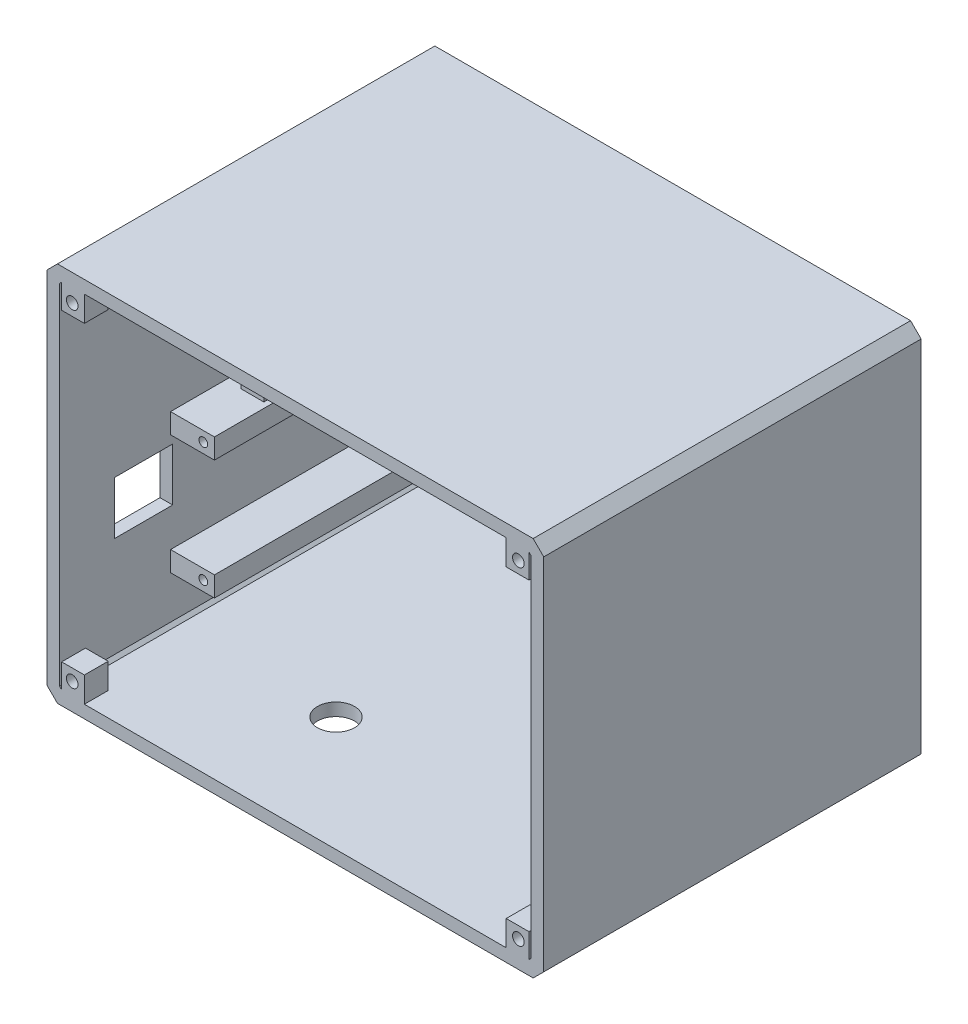
SolidWorks part; units mm, degrees
ref_plane "前视基准面" through (0, 0, 0) normal (0, 0, 1) x (1, 0, 0)
ref_plane "上视基准面" through (0, 0, 0) normal (0, 1, 0) x (1, 0, 0)
ref_plane "右视基准面" through (0, 0, 0) normal (1, 0, 0) x (0, 0, -1)
other "Configuration Table"
sketch "盒底及贯穿安装孔 profile" plane through (0, 0, 0) normal (0, 0, 1) x (1, 0, 0)
  line L0 (-45, -36) -> (45, -36)
  line L1 (45, -36) -> (47, -34)
  line L2 (47, -34) -> (47, 34)
  line L3 (47, 34) -> (45, 36)
  line L4 (45, 36) -> (-45, 36)
  line L5 (-45, 36) -> (-47, 34)
  line L6 (-47, 34) -> (-47, -34)
  line L7 (-47, -34) -> (-45, -36)
  line L8 (-1.8, -33.5) -> (3.8, -33.5)
  line L9 (3.8, -32.1) -> (-1.8, -32.1)
  line L10 (-1.6, 1.2) -> (3.6, 1.2)
  line L11 (3.6, 3) -> (-1.6, 3)
  circle A0 centre (21.1, 3.4) radius 1.3
  circle A1 centre (41.6, 3.4) radius 1.3
  circle A2 centre (-32, 27.5) radius 1.1
  circle A3 centre (-13, 27.5) radius 1.1
  circle A4 centre (-41, -10) radius 2.1
  circle A5 centre (41, -10) radius 2.1
  circle A6 centre (-42, 15) radius 2.1
  circle A7 centre (42, 15) radius 2.1
  arc A8 (3.8, -33.5) -> (3.8, -32.1) centre (3.8, -32.8) ccw
  arc A9 (-1.8, -32.1) -> (-1.8, -33.5) centre (-1.8, -32.8) ccw
  arc A10 (3.6, 1.2) -> (3.6, 3) centre (3.6, 2.1) ccw
  arc A11 (-1.6, 3) -> (-1.6, 1.2) centre (-1.6, 2.1) ccw
extrude "盒底及贯穿安装孔" add sketch "盒底及贯穿安装孔 profile" along normal blind 2.8
sketch "2.4 mm周壁 profile" plane through (0, 0, 0) normal (0, 0, 1) x (1, 0, 0)
  line L0 (-45, -36) -> (45, -36)
  line L1 (45, -36) -> (47, -34)
  line L2 (47, -34) -> (47, 34)
  line L3 (47, 34) -> (45, 36)
  line L4 (45, 36) -> (-45, 36)
  line L5 (-45, 36) -> (-47, 34)
  line L6 (-47, 34) -> (-47, -34)
  line L7 (-47, -34) -> (-45, -36)
  line L8 (-44, -33.6) -> (44, -33.6)
  line L9 (44, -33.6) -> (44.6, -33)
  line L10 (44.6, -33) -> (44.6, 33)
  line L11 (44.6, 33) -> (44, 33.6)
  line L12 (44, 33.6) -> (-44, 33.6)
  line L13 (-44, 33.6) -> (-44.6, 33)
  line L14 (-44.6, 33) -> (-44.6, -33)
  line L15 (-44.6, -33) -> (-44, -33.6)
extrude "2.4 mm周壁" add sketch "2.4 mm周壁 profile" along normal blind 68.6 from offset 2.8
sketch "盒盖上部连接耳 Ø2.2导孔 profile" plane through (0, 0, 0) normal (0, 0, 1) x (1, 0, 0)
  line L0 (-44.2, -34.1) -> (-39.9, -34.1)
  line L1 (-39.9, -34.1) -> (-39.9, -28.8)
  line L2 (-39.9, -28.8) -> (-44.2, -28.8)
  line L3 (-44.2, -28.8) -> (-44.2, -34.1)
  line L4 (-44.2, 28.8) -> (-39.9, 28.8)
  line L5 (-39.9, 28.8) -> (-39.9, 34.1)
  line L6 (-39.9, 34.1) -> (-44.2, 34.1)
  line L7 (-44.2, 34.1) -> (-44.2, 28.8)
  line L8 (39.9, -34.1) -> (44.2, -34.1)
  line L9 (44.2, -34.1) -> (44.2, -28.8)
  line L10 (44.2, -28.8) -> (39.9, -28.8)
  line L11 (39.9, -28.8) -> (39.9, -34.1)
  line L12 (39.9, 28.8) -> (44.2, 28.8)
  line L13 (44.2, 28.8) -> (44.2, 34.1)
  line L14 (44.2, 34.1) -> (39.9, 34.1)
  line L15 (39.9, 34.1) -> (39.9, 28.8)
  circle A0 centre (-42.2, -31) radius 1.1
  circle A1 centre (42.2, -31) radius 1.1
  circle A2 centre (-42.2, 31) radius 1.1
  circle A3 centre (42.2, 31) radius 1.1
extrude "盒盖上部连接耳 Ø2.2导孔" add sketch "盒盖上部连接耳 Ø2.2导孔 profile" along normal blind 4.5 from offset 66.9
sketch "电池垫条 profile" plane through (0, 0, 0) normal (0, 0, 1) x (1, 0, 0)
  line L0 (-28, -31.8) -> (-23, -31.8)
  line L1 (-23, -31.8) -> (-23, -0.3)
  line L2 (-23, -0.3) -> (-28, -0.3)
  line L3 (-28, -0.3) -> (-28, -31.8)
  line L4 (23, -31.8) -> (28, -31.8)
  line L5 (28, -31.8) -> (28, -0.3)
  line L6 (28, -0.3) -> (23, -0.3)
  line L7 (23, -0.3) -> (23, -31.8)
extrude "电池垫条" add sketch "电池垫条 profile" along normal blind 1.2 from offset 2.8
sketch "电池端挡 profile" plane through (0, 0, 0) normal (0, 0, 1) x (1, 0, 0)
  line L0 (-36.5, -31.4) -> (-34.9, -31.4)
  line L1 (-34.9, -31.4) -> (-34.9, -28)
  line L2 (-34.9, -28) -> (-36.5, -28)
  line L3 (-36.5, -28) -> (-36.5, -31.4)
  line L4 (34.9, -31.4) -> (36.5, -31.4)
  line L5 (36.5, -31.4) -> (36.5, -28)
  line L6 (36.5, -28) -> (34.9, -28)
  line L7 (34.9, -28) -> (34.9, -31.4)
extrude "电池端挡" add sketch "电池端挡 profile" along normal blind 3 from offset 2.8
sketch "传感器无排针侧支柱 Ø2.2 贯穿 profile" plane through (0, 0, 0) normal (0, 0, 1) x (1, 0, 0)
  circle A0 centre (-32, 27.5) radius 2.7
  circle A1 centre (-13, 27.5) radius 2.7
  circle A2 centre (-32, 27.5) radius 1.1
  circle A3 centre (-13, 27.5) radius 1.1
extrude "传感器无排针侧支柱 Ø2.2 贯穿" add sketch "传感器无排针侧支柱 Ø2.2 贯穿 profile" along normal blind 11.2 from offset 2.8
sketch "GNSS单边凸台 Ø2.6 贯穿，板内接触3mm profile" plane through (0, 0, 0) normal (0, 0, 1) x (1, 0, 0)
  line L0 (18.45, 1.2) -> (44.2, 1.2)
  line L1 (44.2, 1.2) -> (44.2, 5)
  line L2 (44.2, 5) -> (38.9, 5)
  line L3 (38.9, 5) -> (38.9, 2)
  line L4 (38.9, 2) -> (23.8, 2)
  line L5 (23.8, 2) -> (23.8, 5)
  line L6 (23.8, 5) -> (18.45, 5)
  line L7 (18.45, 5) -> (18.45, 1.2)
  circle A0 centre (21.1, 3.4) radius 1.3
  circle A1 centre (41.6, 3.4) radius 1.3
extrude "GNSS单边凸台 Ø2.6 贯穿，板内接触3mm" add sketch "GNSS单边凸台 Ø2.6 贯穿，板内接触3mm profile" along normal blind 6 from offset 2.8
sketch "上层端部支座根部 profile" plane through (0, 0, 0) normal (0, 0, 1) x (1, 0, 0)
  line L0 (36.3, -24.9) -> (44.9, -24.9)
  line L1 (44.9, -24.9) -> (44.9, -21.1)
  line L2 (44.9, -21.1) -> (36.3, -21.1)
  line L3 (36.3, -21.1) -> (36.3, -24.9)
  line L4 (-44.9, -24.9) -> (-36.3, -24.9)
  line L5 (-36.3, -24.9) -> (-36.3, -21.1)
  line L6 (-36.3, -21.1) -> (-44.9, -21.1)
  line L7 (-44.9, -21.1) -> (-44.9, -24.9)
  line L8 (36.3, -2.3) -> (44.9, -2.3)
  line L9 (44.9, -2.3) -> (44.9, 1.5)
  line L10 (44.9, 1.5) -> (36.3, 1.5)
  line L11 (36.3, 1.5) -> (36.3, -2.3)
  line L12 (-44.9, -2.3) -> (-36.3, -2.3)
  line L13 (-36.3, -2.3) -> (-36.3, 1.5)
  line L14 (-36.3, 1.5) -> (-44.9, 1.5)
  line L15 (-44.9, 1.5) -> (-44.9, -2.3)
extrude "上层端部支座根部" add sketch "上层端部支座根部 profile" along normal blind 41.6 from offset 2.8
sketch "上层端部支座 Ø1.65导孔 profile" plane through (0, 0, 0) normal (0, 0, 1) x (1, 0, 0)
  line L0 (36.3, -24.9) -> (44.9, -24.9)
  line L1 (44.9, -24.9) -> (44.9, -21.1)
  line L2 (44.9, -21.1) -> (36.3, -21.1)
  line L3 (36.3, -21.1) -> (36.3, -24.9)
  line L4 (-44.9, -24.9) -> (-36.3, -24.9)
  line L5 (-36.3, -24.9) -> (-36.3, -21.1)
  line L6 (-36.3, -21.1) -> (-44.9, -21.1)
  line L7 (-44.9, -21.1) -> (-44.9, -24.9)
  line L8 (36.3, -2.3) -> (44.9, -2.3)
  line L9 (44.9, -2.3) -> (44.9, 1.5)
  line L10 (44.9, 1.5) -> (36.3, 1.5)
  line L11 (36.3, 1.5) -> (36.3, -2.3)
  line L12 (-44.9, -2.3) -> (-36.3, -2.3)
  line L13 (-36.3, -2.3) -> (-36.3, 1.5)
  line L14 (-36.3, 1.5) -> (-44.9, 1.5)
  line L15 (-44.9, 1.5) -> (-44.9, -2.3)
  circle A0 centre (-38.4, -23) radius 0.825
  circle A1 centre (-38.4, -0.4) radius 0.825
  circle A2 centre (38.4, -23) radius 0.825
  circle A3 centre (38.4, -0.4) radius 0.825
extrude "上层端部支座 Ø1.65导孔" add sketch "上层端部支座 Ø1.65导孔 profile" along normal blind 6 from offset 44.4
sketch "水平电源托板支柱根部 profile" plane through (0, 0, 0) normal (0, 0, 1) x (1, 0, 0)
  line L0 (-41.65, 1.45) -> (-37.35, 1.45)
  line L1 (-37.35, 1.45) -> (-37.35, 4.6)
  line L2 (-37.35, 4.6) -> (-41.65, 4.6)
  line L3 (-41.65, 4.6) -> (-41.65, 1.45)
  line L4 (-41.65, 30.6) -> (-37.35, 30.6)
  line L5 (-37.35, 30.6) -> (-37.35, 34)
  line L6 (-37.35, 34) -> (-41.65, 34)
  line L7 (-41.65, 34) -> (-41.65, 30.6)
  line L8 (12.85, 1.45) -> (17.15, 1.45)
  line L9 (17.15, 1.45) -> (17.15, 4.6)
  line L10 (17.15, 4.6) -> (12.85, 4.6)
  line L11 (12.85, 4.6) -> (12.85, 1.45)
  line L12 (12.85, 30.6) -> (17.15, 30.6)
  line L13 (17.15, 30.6) -> (17.15, 34)
  line L14 (17.15, 34) -> (12.85, 34)
  line L15 (12.85, 34) -> (12.85, 30.6)
extrude "水平电源托板支柱根部" add sketch "水平电源托板支柱根部 profile" along normal blind 31.2 from offset 2.8
sketch "水平电源托板 Ø1.65导孔 profile" plane through (0, 0, 0) normal (0, 0, 1) x (1, 0, 0)
  line L0 (-41.65, 1.45) -> (-37.35, 1.45)
  line L1 (-37.35, 1.45) -> (-37.35, 4.6)
  line L2 (-37.35, 4.6) -> (-41.65, 4.6)
  line L3 (-41.65, 4.6) -> (-41.65, 1.45)
  line L4 (-41.65, 30.6) -> (-37.35, 30.6)
  line L5 (-37.35, 30.6) -> (-37.35, 34)
  line L6 (-37.35, 34) -> (-41.65, 34)
  line L7 (-41.65, 34) -> (-41.65, 30.6)
  line L8 (12.85, 1.45) -> (17.15, 1.45)
  line L9 (17.15, 1.45) -> (17.15, 4.6)
  line L10 (17.15, 4.6) -> (12.85, 4.6)
  line L11 (12.85, 4.6) -> (12.85, 1.45)
  line L12 (12.85, 30.6) -> (17.15, 30.6)
  line L13 (17.15, 30.6) -> (17.15, 34)
  line L14 (17.15, 34) -> (12.85, 34)
  line L15 (12.85, 34) -> (12.85, 30.6)
  circle A0 centre (-39.5, 3.2) radius 0.825
  circle A1 centre (15, 3.2) radius 0.825
  circle A2 centre (-39.5, 32.2) radius 0.825
  circle A3 centre (15, 32.2) radius 0.825
extrude "水平电源托板 Ø1.65导孔" add sketch "水平电源托板 Ø1.65导孔 profile" along normal blind 6 from offset 34
sketch "Type-C 暂定10×11开口 profile" plane through (0, 0, 0) normal (0, 0, 1) x (1, 0, 0)
  line L0 (-47.3, -14) -> (-44.2, -14)
  line L1 (-44.2, -14) -> (-44.2, -4)
  line L2 (-44.2, -4) -> (-47.3, -4)
  line L3 (-47.3, -4) -> (-47.3, -14)
extrude "Type-C 暂定10×11开口" cut sketch "Type-C 暂定10×11开口 profile" against normal blind 11 from offset 61
sketch "反面天线连接位置 Ø7预留孔 profile" plane through (0, -36, 0) normal (0, -1, 0) x (1, 0, 0)
  circle A0 centre (-14, 49.7) radius 3.5
extrude "反面天线连接位置 Ø7预留孔" cut sketch "反面天线连接位置 Ø7预留孔 profile" against normal blind 2.5
